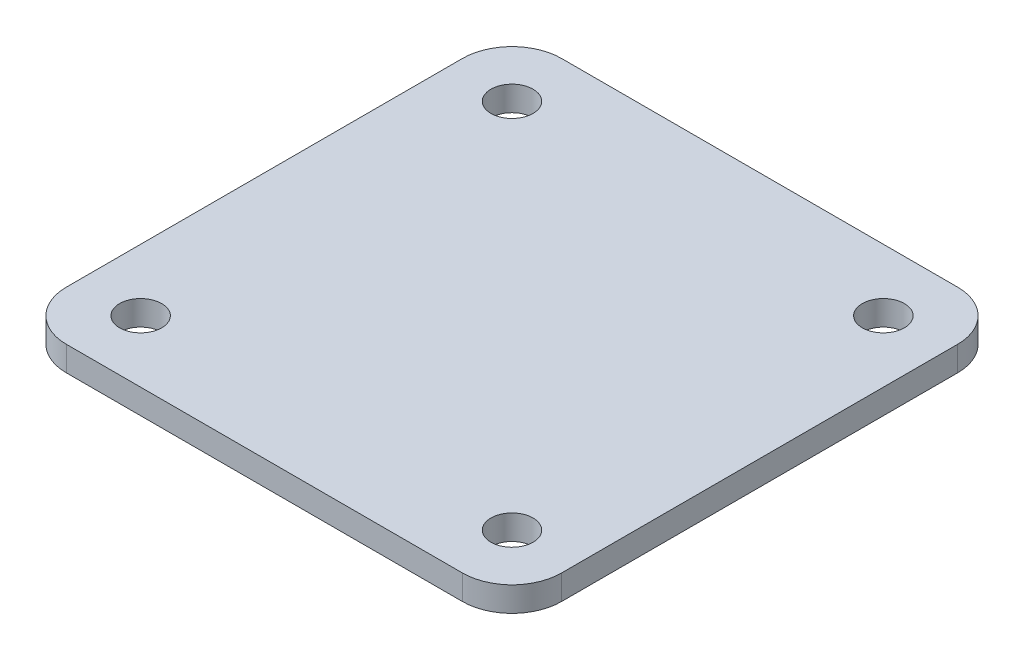
SolidWorks part; units mm, degrees
ref_plane "Front Plane" through (0, 0, 0) normal (0, 0, 1) x (1, 0, 0)
ref_plane "Top Plane" through (0, 0, 0) normal (0, 1, 0) x (1, 0, 0)
ref_plane "Right Plane" through (0, 0, 0) normal (1, 0, 0) x (0, 0, -1)
sketch "Sketch1" plane through (0, 0, 0) normal (0, 1, 0) x (1, 0, 0)
  line L1 (-20, 20) -> (20, 20)
  line L2 (-20, 20) -> (-20, -20)
  line L3 (-20, -20) -> (20, -20)
  line L4 (20, 20) -> (20, -20)
  line L5 (-20, 20) -> (20, -20) construction
  line L6 (-20, -20) -> (20, 20) construction
  line L7 (-15, -15) -> (15, -15) construction
  line L8 (-15, -15) -> (-15, 15) construction
  line L9 (-15, 15) -> (15, 15) construction
  line L10 (15, -15) -> (15, 15) construction
  line L11 (-15, -15) -> (15, 15) construction
  line L12 (-15, 15) -> (15, -15) construction
  circle A0 centre (15, 15) radius 1.7
  circle A1 centre (-15, 15) radius 1.7
  circle A2 centre (-15, -15) radius 1.7
  circle A3 centre (15, -15) radius 1.7
  point P0 (0, 0)
  point P6 (0, 0)
  point P15 (0.308, 0.088)
  point P16 (0, 0)
  dimension "D3" = 3.4
  dimension "D1" = 40
  dimension "D2" = 30
extrude "Boss-Extrude1" add sketch "Sketch1" along normal blind 2
fillet "Fillet1" radius 4 4 edges at (-20, 1, -20) (20, 1, -20) (20, 1, 20) (-20, 1, 20)
